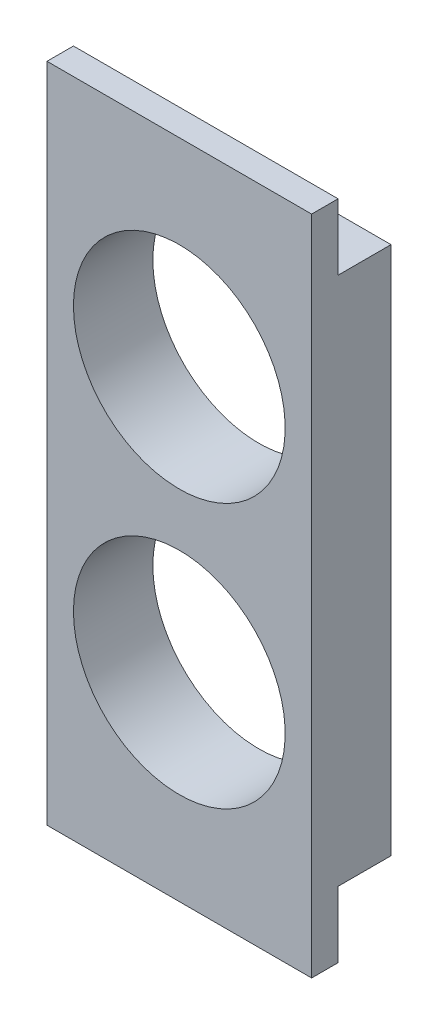
SolidWorks part; units mm, degrees
ref_plane "前视基准面" through (0, 0, 0) normal (0, 0, 1) x (1, 0, 0)
ref_plane "上视基准面" through (0, 0, 0) normal (0, 1, 0) x (1, 0, 0)
ref_plane "右视基准面" through (0, 0, 0) normal (1, 0, 0) x (0, 0, -1)
sketch "草图1" plane through (0, 0, 0) normal (0, 0, 1) x (1, 0, 0)
  line L0 (0, 100) -> (0, -100) construction
  line L1 (50, -100) -> (-50, -100)
  line L2 (50, -100) -> (50, 100)
  line L3 (50, 100) -> (-50, 100)
  line L4 (-50, -100) -> (-50, 100)
  line L5 (50, -100) -> (-50, 100) construction
  line L6 (50, 100) -> (-50, -100) construction
  line L7 (-50, 0) -> (50, 0) construction
  circle A0 centre (0, 50) radius 40
  circle A1 centre (0, -50) radius 40
  point P0 (0, 0)
  dimension "D3" = 80
  dimension "D1" = 100
  dimension "D2" = 200
  dimension "D4" = 50
extrude "凸台-拉伸1" add sketch "草图1" along normal blind 20
sketch "草图2" plane through (0, 0, 20) normal (0, 0, 1) x (1, 0, 0)
  line L0 (-50, 100) -> (-50, -100) construction
  line L1 (50, -125) -> (-50, -125)
  line L2 (50, -125) -> (50, 125)
  line L3 (50, 125) -> (-50, 125)
  line L4 (-50, -125) -> (-50, 125)
  line L5 (50, -125) -> (-50, 125) construction
  line L6 (50, 125) -> (-50, -125) construction
  point P0 (0, 0)
  dimension "D1" = 250
extrude "凸台-拉伸2" add sketch "草图2" along normal blind 10
sketch "草图3" plane through (0, 0, 20) normal (0, 0, -1) x (-1, 0, 0)
  circle A1 centre (0, 50) radius 40
  circle A2 centre (0, 50) radius 40
  circle A3 centre (0, -50) radius 40
  circle A4 centre (0, -50) radius 40
  dimension "D1" = 0
  dimension "D2" = 0
extrude "切除-拉伸1" cut sketch "草图3" against normal through all
